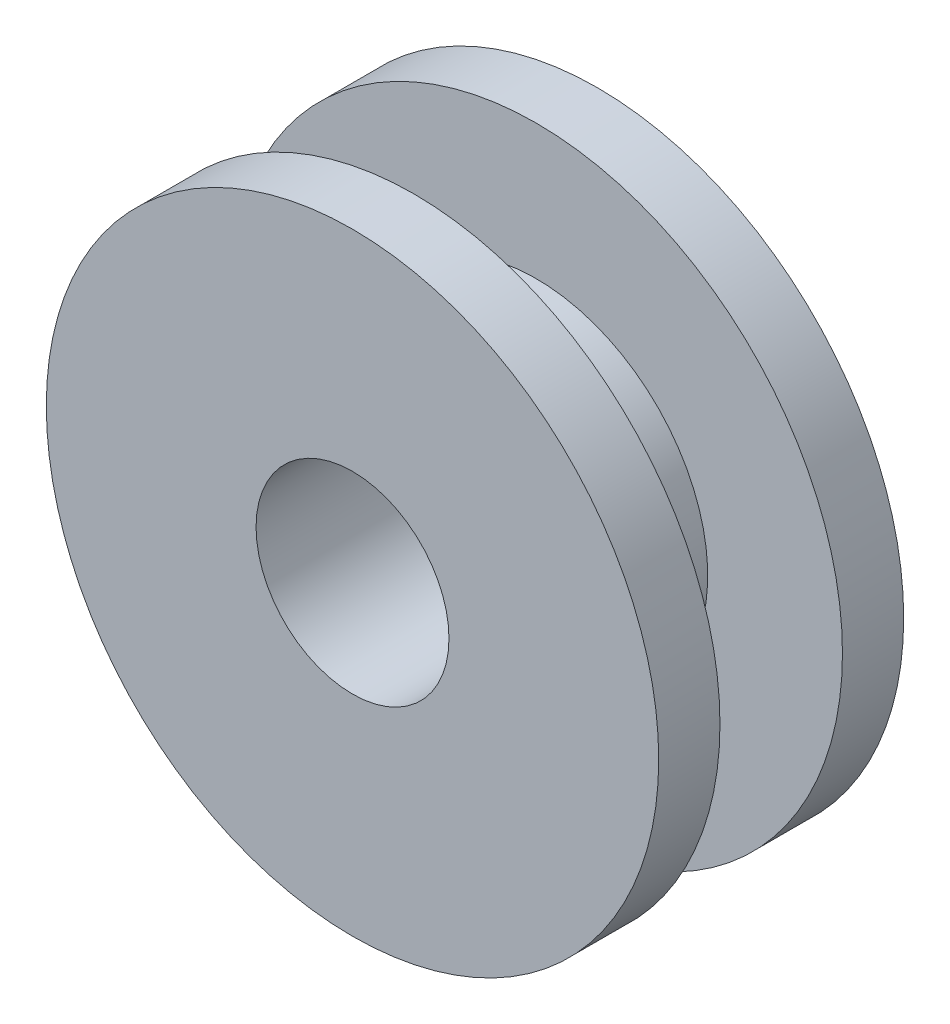
SolidWorks part; units mm, degrees
ref_plane "Front Plane" through (0, 0, 0) normal (0, 0, 1) x (1, 0, 0)
ref_plane "Top Plane" through (0, 0, 0) normal (0, 1, 0) x (1, 0, 0)
ref_plane "Right Plane" through (0, 0, 0) normal (1, 0, 0) x (0, 0, -1)
sketch "Sketch1" plane through (0, 0, 0) normal (0, 0, 1) x (1, 0, 0)
  line L0 (0, 0) -> (0, -2.3) construction
  line L3 (-5, -8) -> (5, -8)
  line L5 (0, -2.3) -> (-3.5, -2.3) construction
  line L6 (-5, 0) -> (-5, -8)
  line L7 (-3.5, -2.3) -> (3.5, -2.3)
  line L8 (-3.5, -2.3) -> (-3.5, -6.3)
  line L9 (-3.5, -6.3) -> (3.5, -6.3)
  line L10 (3.5, -2.3) -> (3.5, -6.3)
  line L11 (5, 0) -> (5, -8)
  circle A1 centre (0, 0) radius 3
  arc A2 (5, 0) -> (-5, 0) centre (0, 0) ccw
  dimension "D1" = 8
  dimension "D4" = 6
  dimension "D5" = 3.5
  dimension "D6" = 7
  dimension "D7" = 4
  dimension "D8" = 2.3
extrude "Boss-Extrude1" add sketch "Sketch1" along normal blind 7
sketch "Sketch2" plane through (0, -8, 0) normal (0, -1, 0) x (1, 0, 0)
  circle A0 centre (0, 4) radius 1.35
  dimension "D1" = 2.7
extrude "Cut-Extrude1" cut sketch "Sketch2" against normal up to surface (1.7 mm away) up to face at (0, -6.3, 3.5)
sketch "Sketch3" plane through (0, 0, 0) normal (0, 0, -1) x (-1, 0, 0)
  circle A0 centre (0, 0) radius 10
  dimension "D1" = 20
extrude "Boss-Extrude2" add sketch "Sketch3" along normal blind 2
sketch "Sketch4" plane through (0, 0, -2) normal (0, 0, -1) x (-1, 0, 0)
  circle A0 centre (0, 0) radius 5.6
  dimension "D1" = 11.2
extrude "Boss-Extrude3" add sketch "Sketch4" along normal blind 4
sketch "Sketch5" plane through (0, 0, -6) normal (0, 0, -1) x (-1, 0, 0)
  circle A0 centre (0, 0) radius 10
  dimension "D1" = 20
extrude "Boss-Extrude4" add sketch "Sketch5" along normal blind 2
sketch "Sketch6" plane through (0, 0, 0) normal (0, 0, 1) x (1, 0, 0)
  circle A0 centre (0, 0) radius 3.15
  dimension "D1" = 6.3
extrude "Cut-Extrude2" cut sketch "Sketch6" against normal through all
sketch "Sketch7" plane through (0, 0, 7) normal (0, 0, 1) x (1, 0, 0)
  circle A0 centre (0, 0) radius 17.6493
extrude "Cut-Extrude3" cut sketch "Sketch7" against normal up to surface (7 mm away) up to face at (-10, 0, 0)
